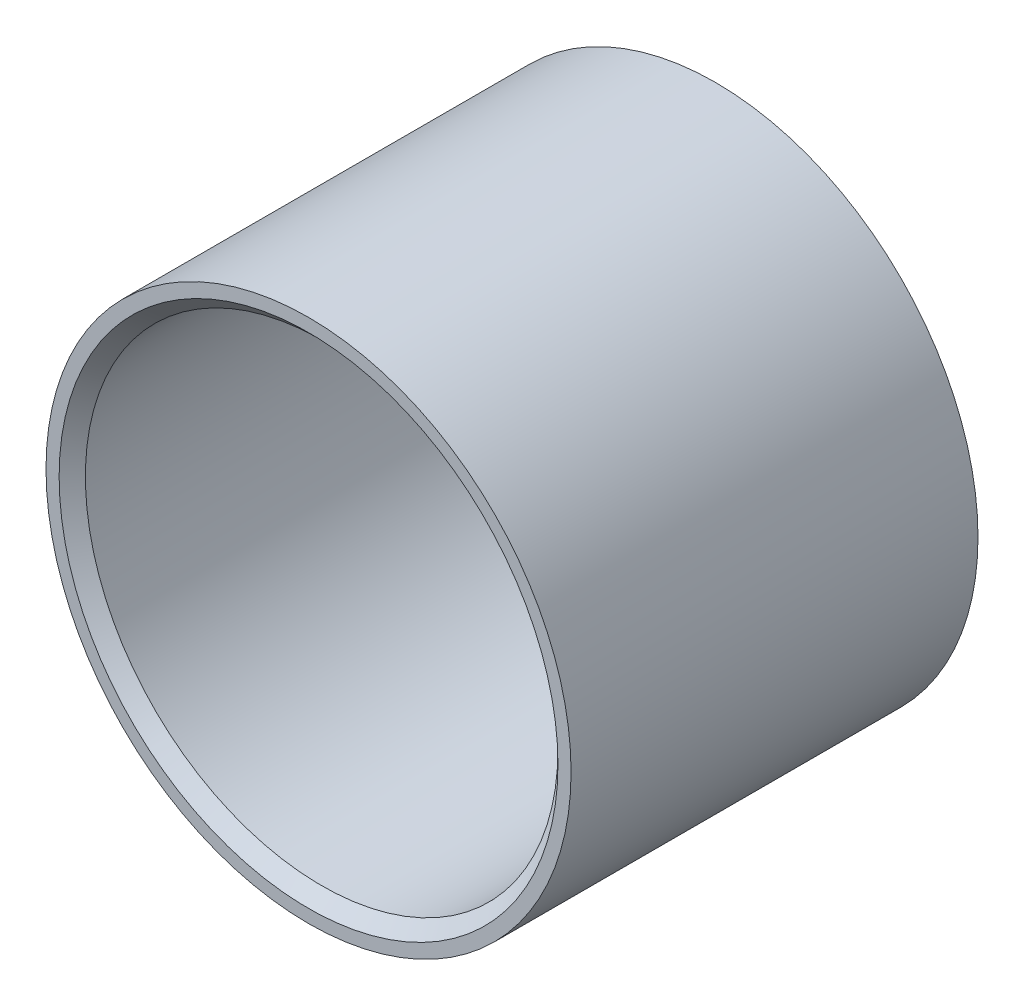
SolidWorks part; units mm, degrees
material "1023 Carbon Steel Sheet (SS)"
ref_plane "Ebene vorne" through (0, 0, 0) normal (0, 0, 1) x (1, 0, 0)
ref_plane "Ebene oben" through (0, 0, 0) normal (0, 1, 0) x (1, 0, 0)
ref_plane "Ebene rechts" through (0, 0, 0) normal (1, 0, 0) x (0, 0, -1)
sketch "Sketch1" plane through (0, 0, 0) normal (0, 0, 1) x (1, 0, 0)
  circle A0 centre (0, 0) radius 9
  circle A1 centre (0, 0) radius 10
  dimension "D1" = 18
  dimension "D2" = 20
extrude "Boss-Extrude1" add sketch "Sketch1" along normal blind 15.5
chamfer "Chamfer2" distance 0.5 angle 45 2 edges at (9, 0, 0) (9, 0, 15.5)
